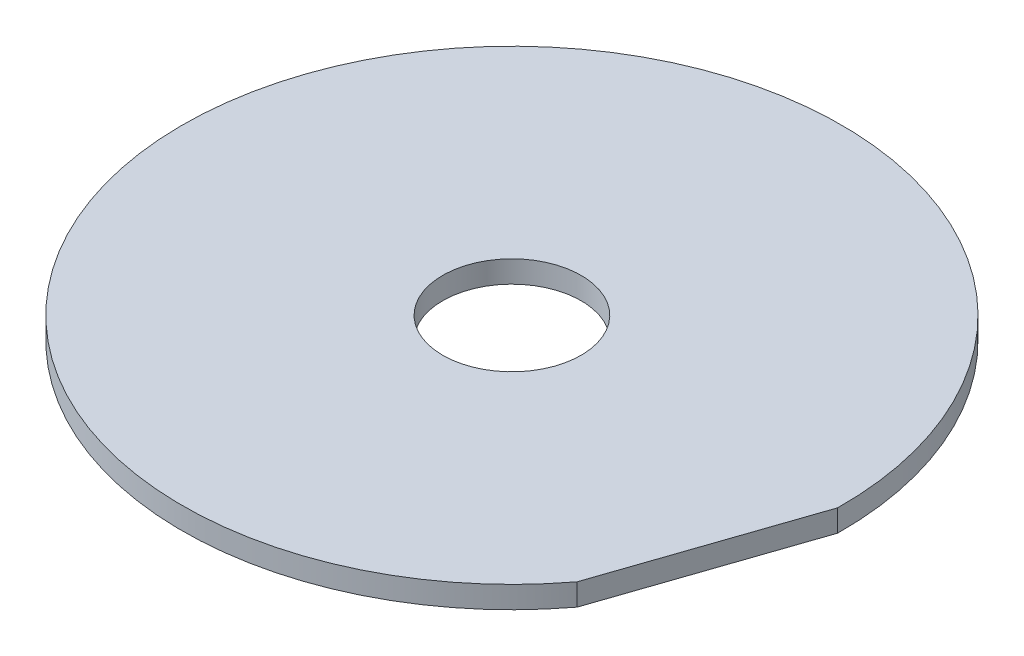
SolidWorks part; units mm, degrees
ref_plane "Ebene vorne" through (0, 0, 0) normal (0, 0, 1) x (1, 0, 0)
ref_plane "Ebene oben" through (0, 0, 0) normal (0, 1, 0) x (1, 0, 0)
ref_plane "Ebene rechts" through (0, 0, 0) normal (1, 0, 0) x (0, 0, -1)
sketch "Skizze1" plane through (0, 0, 0) normal (0, 1, 0) x (1, 0, 0)
  circle A0 centre (0, 0) radius 3.15
  circle A1 centre (0, 0) radius 15
  dimension "D1" = 6.3
  dimension "D2" = 30
extrude "Aufsatz-Linear austragen1" add sketch "Skizze1" along normal blind 1
sketch "Skizze2" plane through (0, 1, 0) normal (0, 1, 0) x (1, 0, 0)
  line L0 (11.9886, -9.0152) -> (14.999, -0.1752)
  line L1 (14.999, -0.1752) -> (16.9767, -0.8487)
  line L2 (16.9767, -0.8487) -> (13.9664, -9.6887)
  line L3 (13.9664, -9.6887) -> (11.9886, -9.0152)
  circle A0 centre (0, 0) radius 15 construction
extrude "Schnitt-Linear austragen1" cut sketch "Skizze2" against normal blind 1
